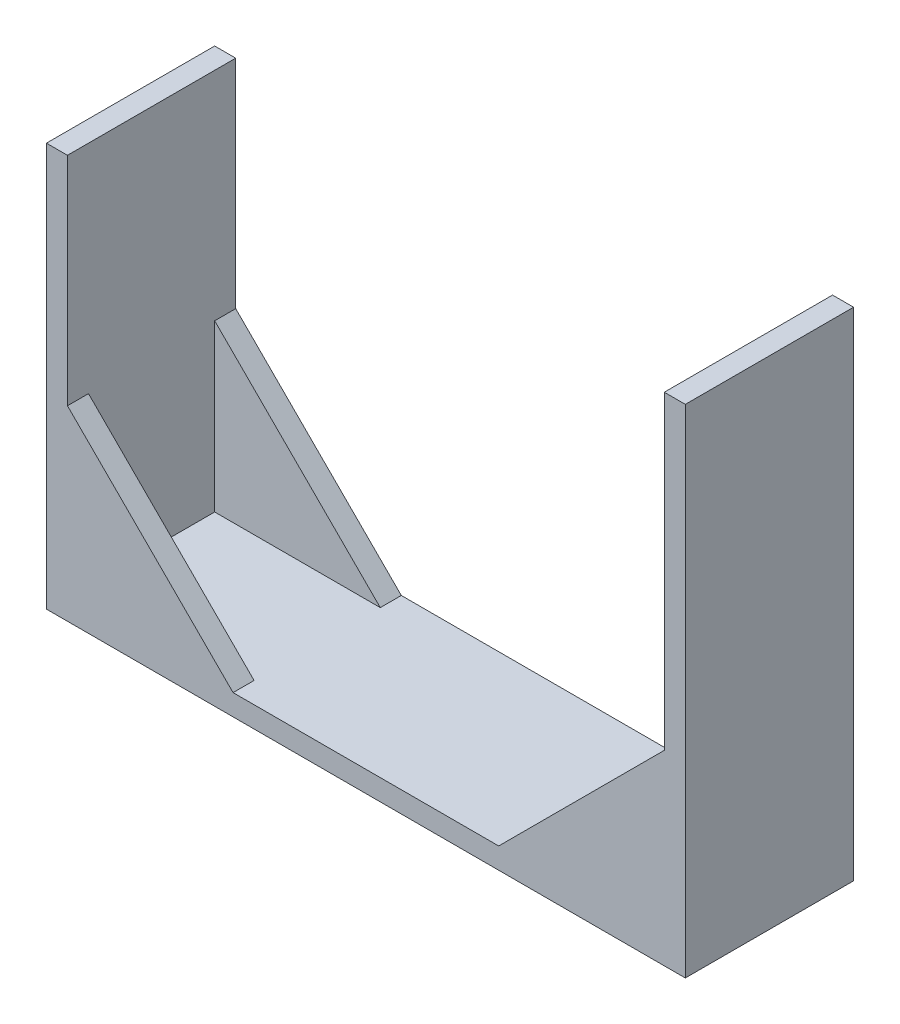
SolidWorks part; units mm, degrees
ref_plane "Front Plane" through (0, 0, 0) normal (0, 0, 1) x (1, 0, 0)
ref_plane "Top Plane" through (0, 0, 0) normal (0, 1, 0) x (1, 0, 0)
ref_plane "Right Plane" through (0, 0, 0) normal (1, 0, 0) x (0, 0, -1)
sketch "Sketch1" plane through (0, 0, 0) normal (0, 0, 1) x (1, 0, 0)
  line L0 (0, 0) -> (385.8, 0)
  line L1 (385.8, 0) -> (385.8, 300)
  line L2 (12.7, 12.7) -> (373.1, 12.7)
  line L3 (373.1, 12.7) -> (373.1, 300)
  line L4 (0, 0) -> (0, 12.7)
  line L5 (385.8, 300) -> (373.1, 300)
  line L6 (12.7, 12.7) -> (12.7, 243.7)
  line L7 (12.7, 243.7) -> (0, 243.7)
  line L8 (0, 243.7) -> (0, 12.7)
  line L9 (0, 12.7) -> (373.1, 12.7) construction
  dimension "D1" = 300
  dimension "D2" = 385.8
  dimension "D4" = 231
  dimension "D3" = 12.7
extrude "Boss-Extrude1" add sketch "Sketch1" along normal mid plane 101.6
sketch "Sketch2" plane through (0, 0, 50.8) normal (0, 0, 1) x (1, 0, 0)
  line L0 (373.1, 112.7) -> (273.1, 12.7)
  line L1 (373.1, 12.7) -> (12.7, 12.7) construction
  line L2 (273.1, 12.7) -> (373.1, 12.7)
  line L3 (373.1, 12.7) -> (373.1, 112.7)
  line L4 (373.1, 300) -> (373.1, 12.7) construction
  line L5 (192.9, 0) -> (192.9, 141.4794) construction
  line L6 (0, 0) -> (385.8, 0) construction
  line L7 (12.7, 12.7) -> (12.7, 112.7)
  line L8 (112.7, 12.7) -> (12.7, 12.7)
  line L9 (12.7, 112.7) -> (112.7, 12.7)
  dimension "D1" = 45
  dimension "D2" = 100
extrude "Boss-Extrude2" add sketch "Sketch2" against normal blind 12.7
mirror "Mirror1" about plane through (0, 0, 0) normal (0, 0, 1) of "Boss-Extrude2"
